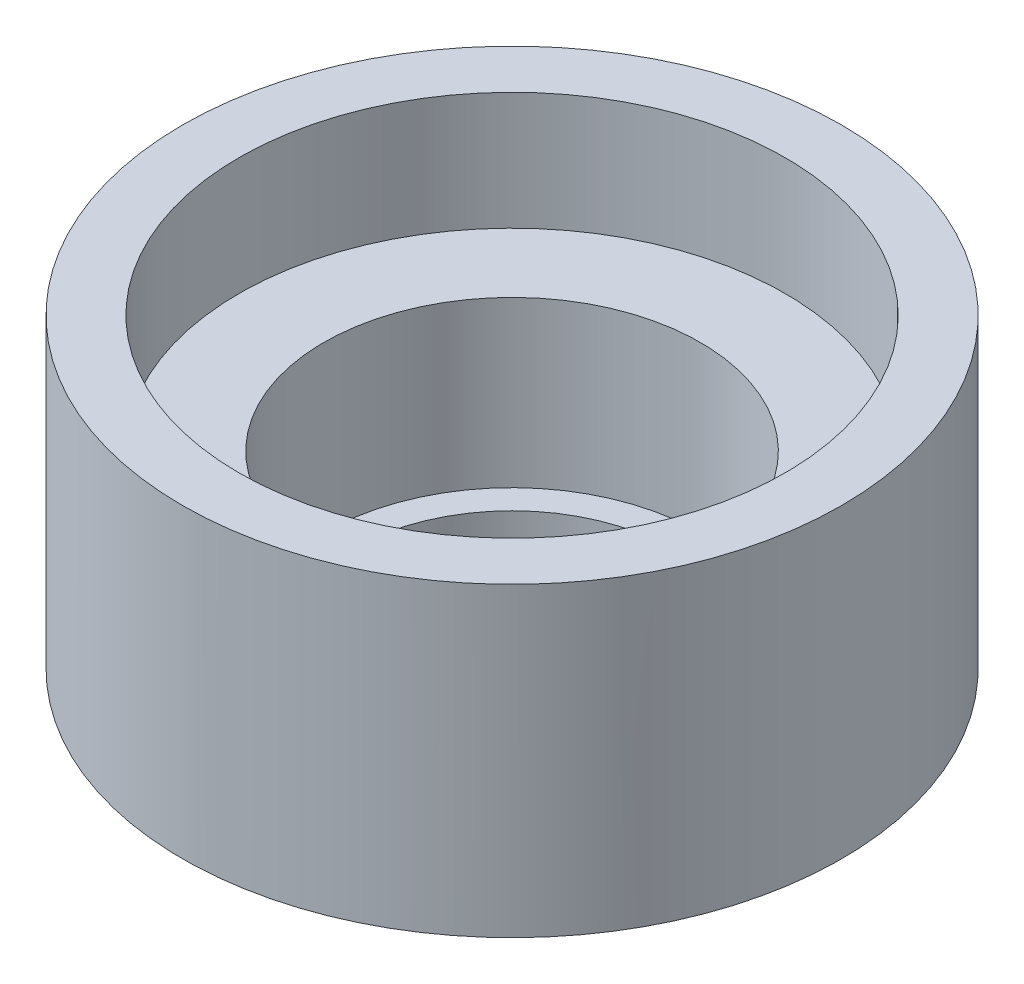
SolidWorks part; units mm, degrees
material "ABS"
ref_plane "Plan de face" through (0, 0, 0) normal (0, 0, 1) x (1, 0, 0)
ref_plane "Plan de dessus" through (0, 0, 0) normal (0, 1, 0) x (1, 0, 0)
ref_plane "Plan de droite" through (0, 0, 0) normal (1, 0, 0) x (0, 0, -1)
sketch "Esquisse3" plane through (0, 0, 0) normal (0, 1, 0) x (1, 0, 0)
  circle A0 centre (0, 0) radius 3.5
  dimension "D1" = 7
extrude "Shape" add sketch "Esquisse3" along normal blind 3.75
sketch "Esquisse4" plane through (0, 3.75, 0) normal (0, 1, 0) x (1, 0, 0)
  circle A0 centre (0, 0) radius 2.9
  dimension "D1" = 5.8
extrude "5_4D" cut sketch "Esquisse4" against normal blind 3
sketch "Esquisse5" plane through (0, 0.75, 0) normal (0, 1, 0) x (1, 0, 0)
  circle A0 centre (0, 0) radius 1.7
  dimension "D1" = 3.4
extrude "3D" cut sketch "Esquisse5" against normal blind 3
sketch "Esquisse6" plane through (0, 0, 0) normal (0, -1, 0) x (1, 0, 0)
  circle A0 centre (0, 0) radius 2.3
  circle A1 centre (0, 0) radius 3.5
  circle A2 centre (0, 0) radius 3.5 construction
  circle A3 centre (0, 0) radius 1.7 construction
  dimension "D1" = 0.6
extrude "Enlèv. mat.-Extru.2" cut sketch "Esquisse6" against normal blind 0.5
sketch "Esquisse9" plane through (0, 0.75, 0) normal (0, 1, 0) x (1, 0, 0)
  circle A0 centre (0, 0) radius 2.9
  circle A1 centre (0, 0) radius 2
  circle A2 centre (0, 0) radius 2.9 construction
  dimension "D1" = 4
extrude "Boss.-Extru.1" add sketch "Esquisse9" along normal blind 1.75
sketch "Esquisse10" plane through (0, 0, 0) normal (0, -1, 0) x (1, 0, 0)
  circle A0 centre (0, 0) radius 2.6192
extrude "ErrorPrinterRemover" cut sketch "Esquisse10" against normal blind 0.2
equation "\"entraxe\"= 2.5mm"
equation "\"D1@Shape\"=\"entretoiseSupportMotor\"+\"entraxe\""
equation "\"entretoiseSupportMotor\"= 1.25mm"
equation "\"entretoiseBearing\"= 1.5mm"
equation "\"length_tibia\"= 206mm"
equation "\"length_femur\"= 117mm"
equation "\"length_coxa\"= 27mm"
equation "\"height\"= 40mm"
equation "\"width\"= 100mm"
equation "\"lever\"= 40mm"
equation "\"errorFlat\"= 0.20mm"
equation "\"errorCircle\"= 0.40mm"
equation "\"cuticule\"=1.5mm"
equation "\"cuticule_attach_w\"=10mm"
equation "\"cuticule_attach_h\"=2.5mm"
equation "\"depthMagnet\"= 1mm"
equation "\"insert_d\" = 3.2mm"
equation "\"insert_l\" = 5mm"
equation "\"D1@Esquisse5\"=\"errorCircle\"+3"
equation "\"D1@Esquisse4\"=\"errorCircle\"+5.4"
equation "\"D1@Esquisse6\"=1-\"errorCircle\""
equation "\"D1@Boss.-Extru.1\"=3-1.25'\"errorFlat\""
equation "\"D1@ErrorPrinterRemover\"=\"errorFlat\""
